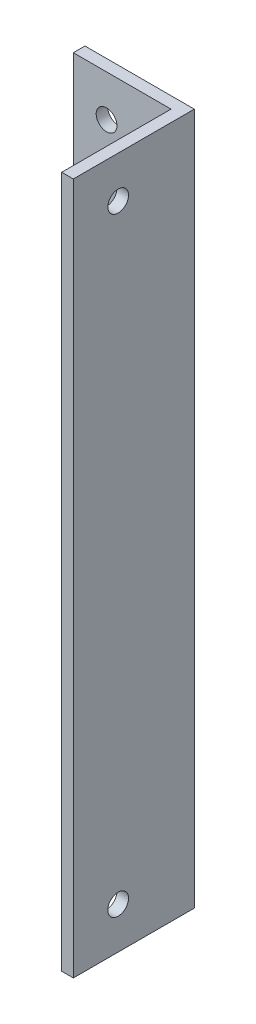
SolidWorks part; units mm, degrees
ref_plane "Plano frontal" through (0, 0, 0) normal (0, 0, 1) x (1, 0, 0)
ref_plane "Plano superior" through (0, 0, 0) normal (0, 1, 0) x (1, 0, 0)
ref_plane "Plano direito" through (0, 0, 0) normal (1, 0, 0) x (0, 0, -1)
sketch "Esboço1" plane through (0, 0, 0) normal (0, 0, 1) x (1, 0, 0)
  line L1 (0, 0) -> (-15.8, 0)
  line L2 (0, 0) -> (0, 100)
  line L3 (0, 100) -> (-15.8, 100)
  line L4 (-15.8, 0) -> (-15.8, 100)
  dimension "D1" = 100
  dimension "D2" = 15.8
extrude "Ressalto-extrusão1" add sketch "Esboço1" along normal blind 1.68
sketch "Esboço3" plane through (0, 0, 1.68) normal (0, 0, 1) x (1, 0, 0)
  line L0 (0, 100) -> (-15.8, 100) construction
  line L1 (0, 0) -> (-1.68, 0)
  line L2 (0, 0) -> (0, 100)
  line L3 (0, 100) -> (-1.68, 100)
  line L4 (-1.68, 0) -> (-1.68, 100)
  dimension "D1" = 1.68
extrude "Ressalto-extrusão2" add sketch "Esboço3" along normal blind 15.8
sketch "Esboço4" plane through (-1.68, 0, 0) normal (-1, 0, 0) x (0, 0, 1)
  line L1 (17.48, 100) -> (1.68, 100) construction
  line L2 (17.48, 0) -> (1.68, 0) construction
  line L3 (1.68, 100) -> (1.68, 0) construction
  circle A0 centre (11, 94) radius 1.5
  circle A1 centre (11, 6) radius 1.5
  dimension "D1" = 3
  dimension "D2" = 9.32
  dimension "D3" = 6
  dimension "D4" = 9.32
  dimension "D5" = 6
  dimension "D6" = 3
extrude "Corte-extrusão1" cut sketch "Esboço4" against normal through all
sketch "Esboço5" plane through (0, 0, 1.68) normal (0, 0, 1) x (1, 0, 0)
  line L1 (-1.68, 100) -> (-15.8, 100) construction
  line L2 (-15.8, 0) -> (-1.68, 0) construction
  line L3 (-1.68, 100) -> (-1.68, 0) construction
  circle A0 centre (-11, 94) radius 1.5
  circle A1 centre (-11, 6) radius 1.5
  dimension "D1" = 9.32
  dimension "D2" = 6
  dimension "D3" = 3
  dimension "D4" = 6
  dimension "D5" = 3
  dimension "D6" = 9.32
extrude "Corte-extrusão2" cut sketch "Esboço5" against normal through all
